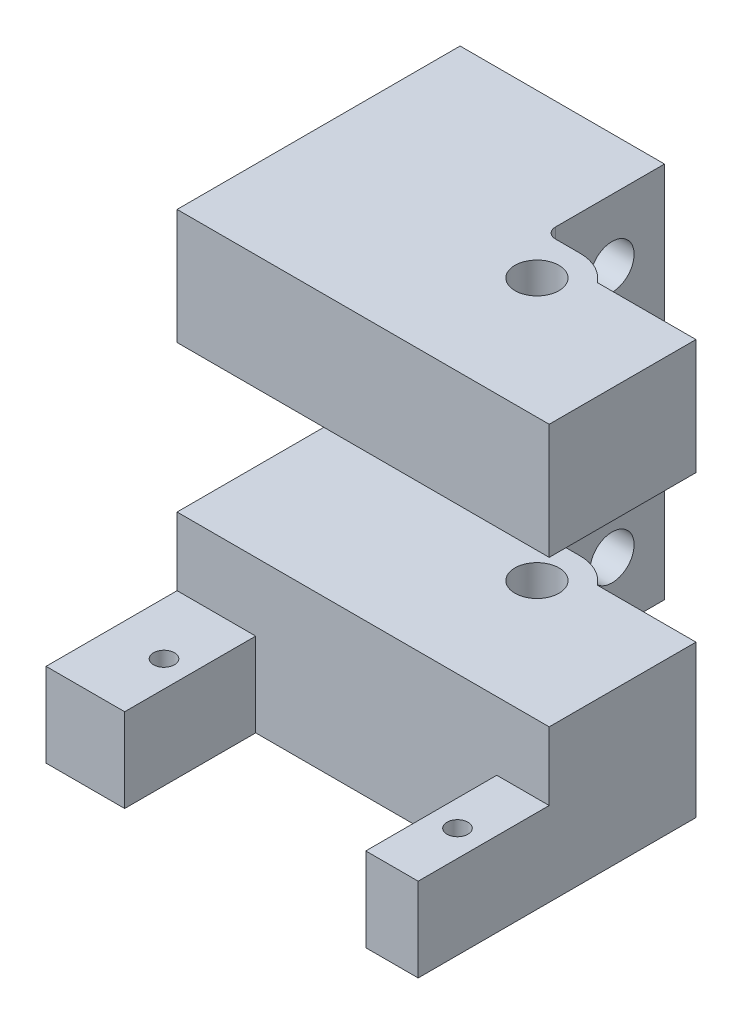
SolidWorks part; units mm, degrees
material "Custom Plastic"
ref_plane "Front Plane" through (0, 0, 0) normal (0, 0, 1) x (1, 0, 0)
ref_plane "Top Plane" through (0, 0, 0) normal (0, 1, 0) x (1, 0, 0)
ref_plane "Right Plane" through (0, 0, 0) normal (1, 0, 0) x (0, 0, -1)
sketch "Sketch1" plane through (0, 0, 0) normal (0, 1, 0) x (1, 0, 0)
  line L0 (-11.5, -6.25) -> (-16.5, -6.25)
  line L2 (11.5, -6.25) -> (11.5, 6.25)
  line L3 (11.5, 6.25) -> (-11.5, 6.25)
  line L4 (-11.5, -6.25) -> (-11.5, 6.25)
  line L5 (11.5, -6.25) -> (-11.5, 6.25) construction
  line L6 (11.5, 6.25) -> (-11.5, -6.25) construction
  line L7 (-16.5, -6.25) -> (-16.5, 21.25)
  line L8 (-16.5, 21.25) -> (16.5, 21.25)
  line L9 (16.5, 21.25) -> (16.5, -6.25)
  line L10 (16.5, -6.25) -> (11.5, -6.25)
  point P0 (0, 0)
  dimension "D1" = 12.5
  dimension "D2" = 23
  dimension "D3" = 5
  dimension "D4" = 5
  dimension "D5" = 15
extrude "Boss-Extrude1" add sketch "Sketch1" along normal blind 16
sketch "Sketch2" plane through (0, 16, 0) normal (0, 1, 0) x (1, 0, 0)
  line L0 (3.5, 21.25) -> (3.5, 24.25) construction
  line L1 (16.5, 21.25) -> (-16.5, 21.25) construction
  line L2 (16.5, -6.25) -> (16.5, 21.25) construction
  line L3 (-1.5, 21.25) -> (-1.5, 24.25)
  line L4 (8.5, 21.25) -> (8.5, 24.25)
  line L5 (-1.5, 24.25) -> (8.5, 24.25) construction
  line L6 (-1.5, 21.25) -> (8.5, 21.25)
  circle A0 centre (3.5, 24.25) radius 2.1
  arc A1 (-1.5, 24.25) -> (8.5, 24.25) centre (3.5, 24.25) cw
  point P11 (3.5, 24.25)
  line M11 (16.5, 21.25) -> (-16.5, 21.25)
  dimension "D2" = 4.2
  dimension "D1" = 13
  dimension "7" = 3
  dimension "D3" = 5
extrude "Boss-Extrude2" [suppressed] add sketch "Sketch2" against normal up to surface (16 mm away) contours A1 L3 L4 A0 M11
sketch "Sketch3" plane through (0, 16, 0) normal (0, 1, 0) x (1, 0, 0)
  line L0 (16.5, 6.25) -> (-16.5, 6.25)
  line L1 (16.5, -6.25) -> (16.5, 21.25) construction
  line L2 (-16.5, 21.25) -> (-16.5, -6.25) construction
  line L3 (-11.5, 6.25) -> (11.5, 6.25) construction
  line L4 (16.5, 21.25) -> (-16.5, 21.25) construction
  line L5 (16.5, 6.25) -> (16.5, 21.25)
  line L6 (16.5, 21.25) -> (-16.5, 21.25)
  line L7 (-16.5, 21.25) -> (-16.5, 6.25)
extrude "Boss-Extrude3" add sketch "Sketch3" along normal blind 6.5
sketch "Sketch6" plane through (0, 22.5, 0) normal (0, 1, 0) x (1, 0, 0)
  line L1 (-26.5, 26.25) -> (-6.5, 26.25)
  line L2 (-6.5, 26.25) -> (-6.5, 21.25)
  line L3 (16.5, 21.25) -> (-16.5, 21.25) construction
  line L5 (-16.5, 21.25) -> (-16.5, 6.25) construction
  line L6 (-26.5, 26.25) -> (-26.5, 21.25)
  line L7 (-26.5, 21.25) -> (-6.5, 21.25)
  dimension "D1" = 20
  dimension "D2" = 10
  dimension "D3" = 5
extrude "Boss-Extrude5" add sketch "Sketch6" along normal blind 25 and the other way up to surface
sketch "Sketch7" plane through (-6.5, 0, 0) normal (1, 0, 0) x (0, 0, -1)
  line L0 (26.25, 11.5) -> (38.25, 11.5)
  line L1 (26.25, 47.5) -> (26.25, 0) construction
  line L2 (38.25, 11.5) -> (38.25, 47.5)
  line L3 (38.25, 47.5) -> (26.25, 47.5)
  line L4 (26.25, 47.5) -> (26.25, 11.5)
  line L6 (6.25, 22.5) -> (21.25, 22.5) construction
  point P8 (26.25, 29.5)
  dimension "D1" = 36
  dimension "D2" = 12
  dimension "D3" = 7
extrude "Boss-Extrude6" add sketch "Sketch7" along normal blind 7 and the other way up to surface other way up to face at (-26.5, 23.75, -23.75)
hole_wizard "Ø3.0mm Dowel Hole2" positions "Sketch12" profile "Sketch13" hole size "Ø3.0" standard "ANSI Metric"
sketch "Sketch12" plane through (0, 0, -21.25) normal (0, 0, 1) x (1, 0, 0)
  line L2 (-6.5, 22.5) -> (-16.5, 22.5) construction
  line L3 (-16.5, 22.5) -> (-16.5, 16) construction
  point P0 (-14, 29)
  dimension "D1" = 6.5
  dimension "D2" = 2.5
sketch "Sketch13" plane through (-14, 29, -21.25) normal (1, 0, 0) x (0, -1, 0)
  line L0 (0, 0) -> (0, 4.999)
  line L1 (0, 4.999) -> (1.5, 4.999)
  line L2 (1.5, 4.999) -> (1.5, 0)
  line L5 (1.5, 0) -> (0, 0)
  line L10 (0, 4.999) -> (-1.5, 4.999) construction
  line L11 (0, -6.35) -> (0, 107.95) construction
  dimension "Hole Dia." = 3
  dimension "Hole Depth" = 4.999
  dimension "Drill Angle" = 180
ref_plane "Plane2" through (0, 36.5, 0) normal (0, 1, 0) x (1, 0, 0)
sketch "Sketch15" plane through (0, 36.5, 0) normal (0, 1, 0) x (1, 0, 0)
  line L0 (-16.5, 21.25) -> (16.5, 21.25)
  line L1 (16.5, 21.25) -> (16.5, -6.25)
  line L2 (16.5, -6.25) -> (-16.5, -6.25)
  line L3 (-16.5, -6.25) -> (-16.5, 21.25)
extrude "Boss-Extrude8" add sketch "Sketch15" along normal blind 11
sketch "Sketch16" plane through (-16.5, 0, 0) normal (-1, 0, 0) x (0, 0, 1)
  line L4 (-21.25, 36.5) -> (6.25, 36.5)
  line L5 (6.25, 36.5) -> (6.25, 47.5)
  line L6 (-21.25, 0) -> (6.25, 0)
  line L7 (6.25, 0) -> (6.25, 16)
  line L8 (6.25, 16) -> (-6.25, 16)
  line L9 (-6.25, 16) -> (-6.25, 22.5)
  line L10 (-6.25, 22.5) -> (-21.25, 22.5)
  line L11 (-21.25, 22.5) -> (-21.25, 0)
  line L12 (-21.25, 0) -> (6.25, 0)
  line L13 (6.25, 0) -> (6.25, 16)
  line L14 (6.25, 16) -> (-6.25, 16)
  line L15 (-6.25, 16) -> (-6.25, 22.5)
  line L16 (-6.25, 22.5) -> (-21.25, 22.5)
  line L17 (-21.25, 22.5) -> (-21.25, 0)
  line L18 (6.25, 47.5) -> (-21.25, 47.5)
  line L19 (-21.25, 47.5) -> (-21.25, 36.5)
  line L20 (-21.25, 36.5) -> (6.25, 36.5)
  line L21 (6.25, 36.5) -> (6.25, 47.5)
  line L22 (6.25, 47.5) -> (-21.25, 47.5)
  line L23 (-21.25, 47.5) -> (-21.25, 36.5)
  dimension "D1" = 0
  dimension "D2" = 0
extrude "Boss-Extrude9" add sketch "Sketch16" along normal up to surface (10 mm away)
sketch "Sketch17" plane through (-6.5, 0, 0) normal (1, 0, 0) x (0, 0, -1)
  line L7 (21.25, 0) -> (26.25, 0)
  line L8 (26.25, 0) -> (26.25, 11.5)
  line L9 (26.25, 11.5) -> (26.25, 47.5)
  line L10 (26.25, 47.5) -> (21.25, 47.5)
  line L11 (21.25, 47.5) -> (21.25, 36.5)
  line L12 (21.25, 36.5) -> (21.25, 22.5)
  line L13 (21.25, 22.5) -> (21.25, 0)
  line L14 (21.25, 0) -> (26.25, 0)
  line L15 (26.25, 0) -> (26.25, 11.5)
  line L16 (26.25, 11.5) -> (26.25, 47.5)
  line L17 (26.25, 47.5) -> (21.25, 47.5)
  line L19 (21.25, 36.5) -> (21.25, 22.5)
  line L20 (21.25, 22.5) -> (21.25, 0)
  line L21 (21.25, 47.5) -> (21.25, 36.5)
  dimension "D1" = 0
extrude "Boss-Extrude10" add sketch "Sketch17" along normal up to surface (7 mm away)
sketch "Sketch20" plane through (-26.5, 0, 0) normal (-1, 0, 0) x (0, 0, 1)
  line L12 (-26.25, 0) -> (6.25, 0)
  line L13 (6.25, 0) -> (6.25, 16)
  line L14 (6.25, 0) -> (6.25, 16)
  line L15 (6.25, 16) -> (-6.25, 16)
  line L16 (6.25, 16) -> (-6.25, 16)
  line L17 (-21.25, 22.5) -> (-21.25, 36.5)
  line L18 (-6.25, 16) -> (-6.25, 22.5)
  line L19 (-6.25, 16) -> (-6.25, 22.5)
  line L20 (6.25, 47.5) -> (-38.25, 47.5)
  line L21 (-38.25, 47.5) -> (-38.25, 11.5)
  line L22 (-38.25, 11.5) -> (-26.25, 11.5)
  line L23 (-26.25, 11.5) -> (-26.25, 0)
  line L29 (-21.25, 22.5) -> (-21.25, 36.5)
  line L32 (6.25, 47.5) -> (-38.25, 47.5)
  line L33 (-38.25, 47.5) -> (-38.25, 11.5)
  line L34 (-38.25, 11.5) -> (-26.25, 11.5)
  line L35 (-26.25, 11.5) -> (-26.25, 0)
  line L36 (-6.25, 22.5) -> (-21.25, 22.5)
  line L37 (-6.25, 22.5) -> (-21.25, 22.5)
  line L38 (-21.25, 36.5) -> (6.25, 36.5)
  line L39 (-21.25, 36.5) -> (6.25, 36.5)
  line L42 (-26.25, 0) -> (6.25, 0)
  line L44 (6.25, 36.5) -> (6.25, 47.5)
  line L45 (6.25, 36.5) -> (6.25, 47.5)
  dimension "D1" = 0
extrude "Cut-Extrude2" cut sketch "Sketch20" against normal offset from surface (7.5 mm away) 7.5
sketch "Sketch21" plane through (0, 0, 6.25) normal (0, 0, 1) x (1, 0, 0)
  line L4 (-19, 47.5) -> (-19, 36.5)
  line L5 (-19, 36.5) -> (16.5, 36.5)
  line L6 (16.5, 36.5) -> (16.5, 47.5)
  line L7 (16.5, 47.5) -> (-19, 47.5)
  line L9 (-19, 36.5) -> (16.5, 36.5)
  line L10 (16.5, 36.5) -> (16.5, 47.5)
  line L11 (16.5, 47.5) -> (-19, 47.5)
  line L13 (-19, 47.5) -> (-19, 36.5)
  dimension "D1" = 0
extrude "Cut-Extrude3" cut sketch "Sketch21" against normal up to surface (12.5 mm away)
sketch "Sketch22" plane through (0, 0, 0) normal (0, -1, 0) x (1, 0, 0)
  line L17 (-19, 6.25) -> (-19, -26.25)
  line L18 (-19, -26.25) -> (0.5, -26.25)
  line L19 (0.5, -26.25) -> (0.5, -21.25)
  line L20 (0.5, -21.25) -> (16.5, -21.25)
  line L21 (16.5, -21.25) -> (16.5, 6.25)
  line L22 (16.5, 6.25) -> (11.5, 6.25)
  line L23 (11.5, 6.25) -> (11.5, -6.25)
  line L24 (11.5, -6.25) -> (-11.5, -6.25)
  line L25 (-11.5, -6.25) -> (-11.5, 6.25)
  line L26 (-11.5, 6.25) -> (-19, 6.25)
  line L28 (-19, -26.25) -> (0.5, -26.25)
  line L30 (0.5, -21.25) -> (16.5, -21.25)
  line L31 (16.5, -21.25) -> (16.5, 6.25)
  line L32 (16.5, 6.25) -> (11.5, 6.25)
  line L33 (11.5, 6.25) -> (11.5, -6.25)
  line L34 (11.5, -6.25) -> (-11.5, -6.25)
  line L35 (-11.5, -6.25) -> (-11.5, 6.25)
  line L36 (-11.5, 6.25) -> (-19, 6.25)
  line L38 (0.5, -26.25) -> (0.5, -21.25)
  line L41 (-19, 6.25) -> (-19, -26.25)
  dimension "D1" = 0
extrude "Cut-Extrude4" cut sketch "Sketch22" against normal blind 8
sketch "Sketch24" plane through (0, 8, 0) normal (0, -1, 0) x (1, 0, 0)
  line L0 (0.5, -26.25) -> (0.5, -21.25) construction
  line L1 (-19, -26.25) -> (0.5, -26.25) construction
  line L2 (-19, 6.25) -> (-19, -26.25) construction
  line L3 (0.5, -26.25) -> (0.5, -21.25)
  line L4 (-19, -26.25) -> (0.5, -26.25)
  line L5 (-19, -21.25) -> (-19, -26.25)
  line L6 (0.5, -21.25) -> (-19, -21.25)
extrude "Cut-Extrude6" cut sketch "Sketch24" against normal up to surface (3.5 mm away)
sketch "Sketch25" plane through (0, 0, -21.25) normal (0, 0, -1) x (-1, 0, 0)
  line L0 (-16.5, 8) -> (19, 8) construction
  line L1 (19, 8) -> (19, 11.5) construction
  line L2 (19, 11.5) -> (-0.5, 11.5) construction
  line L3 (-0.5, 11.5) -> (-0.5, 22.5) construction
  line L4 (-0.5, 22.5) -> (-16.5, 22.5) construction
  line L5 (-16.5, 22.5) -> (-16.5, 8) construction
  line L6 (-16.5, 36.5) -> (-0.5, 36.5) construction
  line L7 (-0.5, 36.5) -> (-0.5, 47.5) construction
  line L8 (-0.5, 47.5) -> (-16.5, 47.5) construction
  line L9 (-16.5, 47.5) -> (-16.5, 36.5) construction
  line L10 (-16.5, 8) -> (19, 8)
  line L11 (19, 8) -> (19, 11.5)
  line L12 (19, 11.5) -> (-0.5, 11.5)
  line L13 (-0.5, 11.5) -> (-0.5, 22.5)
  line L14 (-0.5, 22.5) -> (-16.5, 22.5)
  line L15 (-16.5, 22.5) -> (-16.5, 8)
  line L16 (-16.5, 36.5) -> (-0.5, 36.5)
  line L17 (-0.5, 36.5) -> (-0.5, 47.5)
  line L18 (-0.5, 47.5) -> (-16.5, 47.5)
  line L19 (-16.5, 47.5) -> (-16.5, 36.5)
extrude "Boss-Extrude11" add sketch "Sketch25" along normal offset from surface (4 mm away) 13
hole_wizard "Ø3.0mm Dowel Hole3" positions "Sketch27" profile "Sketch28" hole size "Ø3.0" standard "ANSI Metric"
sketch "Sketch27" plane through (0, 8, 0) normal (0, -1, 0) x (-1, 0, 0)
  line L0 (-16.5, 25.25) -> (19, 25.25) construction
  line L1 (-16.5, 25.25) -> (-16.5, -6.25) construction
  point P0 (-3.8323, 22.75)
  dimension "D1" = 2.5
  dimension "D2" = 12.6677
sketch "Sketch28" plane through (3.8323, 8, -22.75) normal (1, 0, 0) x (0, 0, -1)
  line L0 (0, 0) -> (0, 39.499)
  line L1 (0, 39.499) -> (2.1, 39.499)
  line L2 (2.1, 39.499) -> (2.1, 0)
  line L5 (2.1, 0) -> (0, 0)
  line L10 (0, 39.499) -> (-2.1, 39.499) construction
  line L11 (0, -6.35) -> (0, 107.95) construction
  dimension "Hole Dia." = 4.2
  dimension "Hole Depth" = 39.499
  dimension "Drill Angle" = 180
sketch "Sketch29" plane through (0, 0, -6.25) normal (0, 0, 1) x (1, 0, 0)
  line L0 (-11.5, 8) -> (11.5, 8) construction
  line L1 (11.5, 8) -> (11.5, 16) construction
  line L2 (11.5, 16) -> (16.5, 16) construction
  line L3 (16.5, 16) -> (16.5, 22.5) construction
  line L4 (16.5, 22.5) -> (-19, 22.5) construction
  line L5 (-19, 22.5) -> (-19, 16) construction
  line L6 (-19, 16) -> (-11.5, 16) construction
  line L7 (-11.5, 16) -> (-11.5, 8) construction
  line L8 (-19, 47.5) -> (-19, 36.5) construction
  line L9 (-19, 36.5) -> (16.5, 36.5) construction
  line L10 (16.5, 36.5) -> (16.5, 47.5) construction
  line L11 (16.5, 47.5) -> (-19, 47.5) construction
  line L12 (-11.5, 8) -> (11.5, 8)
  line L13 (11.5, 8) -> (11.5, 16)
  line L14 (11.5, 16) -> (16.5, 16)
  line L15 (16.5, 16) -> (16.5, 22.5)
  line L16 (16.5, 22.5) -> (-19, 22.5)
  line L17 (-19, 22.5) -> (-19, 16)
  line L18 (-19, 16) -> (-11.5, 16)
  line L19 (-11.5, 16) -> (-11.5, 8)
  line L20 (-19, 47.5) -> (-19, 36.5)
  line L21 (-19, 36.5) -> (16.5, 36.5)
  line L22 (16.5, 36.5) -> (16.5, 47.5)
  line L23 (16.5, 47.5) -> (-19, 47.5)
extrude "Cut-Extrude7" cut sketch "Sketch29" against normal blind 5
sketch "Sketch30" plane through (0, 0, 6.25) normal (0, 0, 1) x (1, 0, 0)
  line L0 (11.5, 8) -> (16.5, 8) construction
  line L1 (16.5, 8) -> (16.5, 16) construction
  line L2 (16.5, 16) -> (11.5, 16) construction
  line L3 (11.5, 16) -> (11.5, 8) construction
  line L4 (-19, 8) -> (-11.5, 8) construction
  line L5 (-11.5, 8) -> (-11.5, 16) construction
  line L6 (-11.5, 16) -> (-19, 16) construction
  line L7 (-19, 16) -> (-19, 8) construction
  line L8 (11.5, 8) -> (16.5, 8)
  line L9 (16.5, 8) -> (16.5, 16)
  line L10 (16.5, 16) -> (11.5, 16)
  line L11 (11.5, 16) -> (11.5, 8)
  line L12 (-19, 8) -> (-11.5, 8)
  line L13 (-11.5, 8) -> (-11.5, 16)
  line L14 (-11.5, 16) -> (-19, 16)
  line L15 (-19, 16) -> (-19, 8)
extrude "Cut-Extrude8" cut sketch "Sketch30" against normal blind 5
sketch "Sketch19" plane through (0, 16, 0) normal (0, 1, 0) x (1, 0, 0)
  line L0 (11.5, 11.25) -> (11.5, -1.25) construction
  line L1 (0, 0) -> (0, 11.25) construction
  line L3 (-19, 11.25) -> (-19, -1.25) construction
  line L4 (16.5, 11.25) -> (-19, 11.25) construction
  circle A1 centre (14, 5) radius 1
  circle A2 centre (-14, 5) radius 1
  point P0 (0, 11.25)
  point P14 (-19, 5)
  dimension "D1" = 2
  dimension "D2" = 2.5
extrude "Cut-Extrude1" cut sketch "Sketch19" against normal blind 8
sketch "Sketch31" plane through (0, 22.5, 0) normal (0, 1, 0) x (1, 0, 0)
  line L17 (0.5, 21.25) -> (-19, 21.25) construction
  line L19 (0.5, 38.25) -> (0.5, 25.25) construction
  line L20 (0.5, 25.25) -> (16.5, 25.25) construction
  line L21 (0.5, 29.25) -> (0.5, 21.25)
  line L24 (-9, 21.25) -> (-9, 26.25) construction
  line L25 (-15.5, 21.25) -> (-12.5, 21.25) construction
  line L26 (-19, 38.25) -> (-19, 11.25) construction
  line L27 (0.5, 29.25) -> (-9, 26.25)
  line L28 (-9, 26.25) -> (-19, 26.25)
  line L29 (-19, 26.25) -> (-19, 21.25)
  line L30 (-19, 21.25) -> (0.5, 21.25)
  dimension "D1" = 4
  dimension "D3" = 5
  dimension "D2" = 10
extrude "Cut-Extrude9" cut sketch "Sketch31" along normal up to surface (14 mm away)
ref_plane "Plane3" through (0, 29.5, 0) normal (0, -1, 0) x (-1, 0, 0)
sketch "Sketch32" plane through (0, 11.5, 0) normal (0, -1, 0) x (1, 0, 0)
  line L0 (3.8323, -26.85) -> (0.5, -26.85)
  line L1 (0.5, -25.25) -> (0.5, -38.25) construction
  line L2 (0.5, -26.85) -> (0.5, -25.25)
  line L3 (0.5, -25.25) -> (7.0819, -25.25)
  line L4 (16.5, -25.25) -> (-19, -25.25) construction
  arc A0 (3.8323, -26.85) -> (7.0819, -25.25) centre (3.8323, -22.75) ccw
  circle A1 centre (3.8323, -22.75) radius 2.1 construction
  dimension "D1" = 2
extrude "Boss-Extrude12" add sketch "Sketch32" against normal offset from surface (11 mm away) 7
mirror "Mirror2" about plane through (0, 29.5, 0) normal (0, -1, 0) of "Boss-Extrude12"
fillet "Fillet1" radius 1 3 edges at (0.5, 17, -26.85) (0.5, 29.5, -29.25) (0.5, 42, -26.85)
sketch "Sketch33" plane through (0, 8, 0) normal (0, -1, 0) x (1, 0, 0)
  circle A0 centre (3.8323, -22.75) radius 4.1
  arc A1 (3.8323, -26.85) -> (7.0819, -25.25) centre (3.8323, -22.75) ccw construction
  circle A2 centre (3.8323, -22.75) radius 2.1 construction
  circle A3 centre (3.8323, -22.75) radius 2.1
extrude "Boss-Extrude13" add sketch "Sketch33" against normal up to surface (3.5 mm away)
hole_wizard "Ø4.2mm Dowel Hole1" positions "Sketch10" profile "Sketch11" hole size "Ø3.0" standard "ANSI Metric"
sketch "Sketch10" plane through (0.5, 0, 0) normal (1, 0, 0) x (0, 0, -1)
  line L0 (33.25, 47.5) -> (33.25, 11.5) construction
  line L5 (25.25, 22.5) -> (25.25, 8) construction
  line L6 (27.85, 11.5) -> (38.25, 11.5) construction
  line L7 (38.25, 47.5) -> (27.85, 47.5) construction
  point P15 (33.25, 41.5)
  point P17 (33.25, 17.5)
  point P18 (33.25, 29.5)
  point P21 (33.25, 11.5)
  point P24 (33.25, 47.5)
  dimension "D1" = 8
  dimension "D2" = 6
  dimension "D3" = 6
sketch "Sketch11" plane through (0.5, 29.5, -33.25) normal (0, 1, 0) x (0, 0, -1)
  line L0 (0, 0) -> (0, 17.5)
  line L1 (0, 17.5) -> (2.1, 17.5)
  line L2 (2.1, 17.5) -> (2.1, 0)
  line L5 (2.1, 0) -> (0, 0)
  line L10 (0, 17.5) -> (-2.1, 17.5) construction
  line L11 (0, -6.35) -> (0, 107.95) construction
  dimension "Hole Dia." = 4.2
  dimension "Hole Depth" = 17.5
  dimension "Drill Angle" = 180
